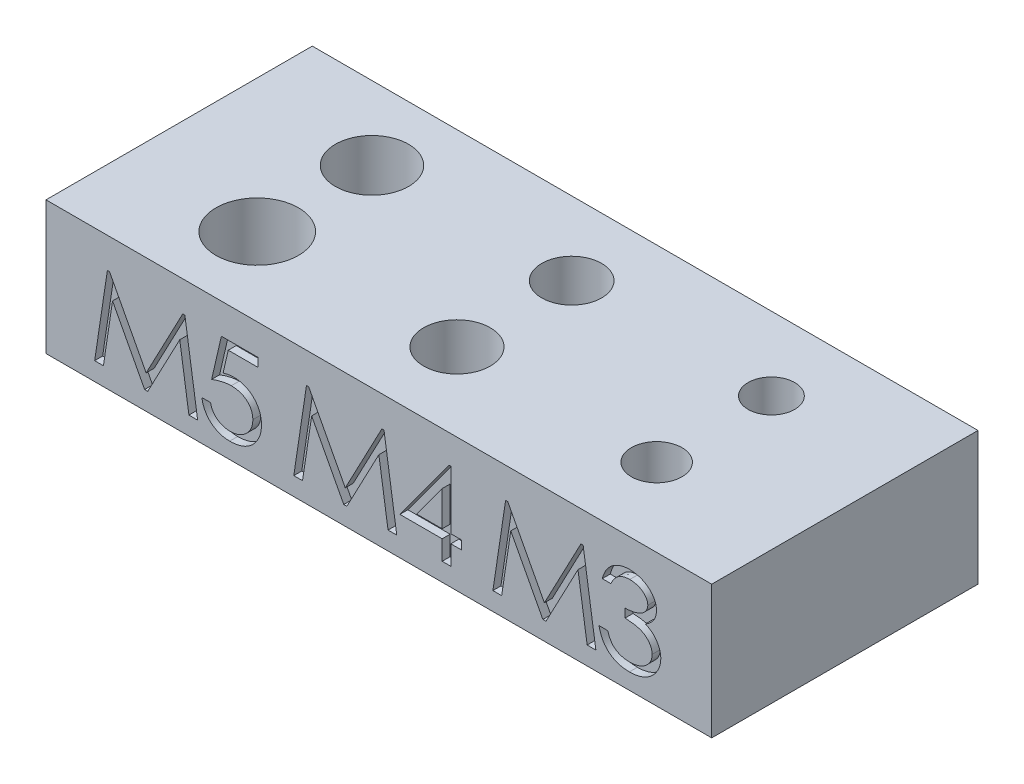
SolidWorks part; units mm, degrees
ref_plane "Front" through (0, 0, 0) normal (0, 0, 1) x (1, 0, 0)
ref_plane "Top" through (0, 0, 0) normal (0, 1, 0) x (1, 0, 0)
ref_plane "Right" through (0, 0, 0) normal (1, 0, 0) x (0, 0, -1)
sketch "Sketch1" plane through (0, 0, 0) normal (0, 1, 0) x (1, 0, 0)
  line L1 (0, 0) -> (50, 0)
  line L2 (0, 0) -> (0, 20)
  line L3 (0, 20) -> (50, 20)
  line L4 (50, 0) -> (50, 20)
  point P4 (0, 0)
  dimension "D1" = 50
  dimension "D2" = 20
extrude "Boss-Extrude1" add sketch "Sketch1" along normal blind 10
sketch "Sketch2" plane through (0, 10, 0) normal (0, 1, 0) x (1, 0, 0)
  line L0 (10, 17.2333) -> (10, 20) construction
  line L2 (25, 0) -> (25, 5.8667) construction
  line L3 (0, 0) -> (50, 0) construction
  line L4 (25, 5.8667) -> (25, 14.4833) construction
  line L5 (25, 14.4833) -> (25, 20) construction
  line L6 (50, 20) -> (0, 20) construction
  line L7 (10, 14.4833) -> (40, 14.4833) construction
  line L8 (10, 5.8667) -> (40, 5.8667) construction
  line L9 (10, 11.7333) -> (10, 8.9667) construction
  line L10 (10, 2.7667) -> (10, 0) construction
  circle A0 centre (10, 14.4833) radius 2.75
  circle A1 centre (25, 14.4833) radius 2.25
  circle A2 centre (40, 14.4833) radius 1.75
  circle A3 centre (10, 5.8667) radius 3.1
  circle A4 centre (25, 5.8667) radius 2.5
  circle A5 centre (40, 5.8667) radius 1.9
  point P26 (25, 5.8667)
  point P28 (25, 14.4833)
  dimension "D2" = 5.5
  dimension "D3" = 6.2
  dimension "D4" = 4.5
  dimension "D5" = 5
  dimension "D6" = 3.5
  dimension "D7" = 3.8
  dimension "D1" = 30
extrude "Cut-Extrude1" cut sketch "Sketch2" against normal through all
sketch "Sketch3" plane through (0, 0, 0) normal (0, 0, 1) x (1, 0, 0)
  line L0 (3.0852, 1.3647) -> (45.4109, 1.3647) construction
  text T0 "M5 M4 M3" font "Century Gothic" height 6.35
  point P3 (1.6652, 7.7505)
  point P4 (45.4109, 7.2661)
  point P5 (4.8055, 7.0911)
  point P6 (0, 0)
  point P7 (3.0852, 5.875)
extrude "Cut-Extrude2" cut sketch "Sketch3" against normal blind 0.6
sketch "Sketch4" plane through (0, 0, 0) normal (-1, 0, 0) x (0, 0, 1)
  line L0 (-17.0905, 1.2868) -> (-4.1179, 1.2868) construction
  text T0 "S I" font "Century Gothic" height 6.35
  point P3 (-17.0905, 7.9943)
extrude "Cut-Extrude3" cut sketch "Sketch4" against normal blind 0.6
